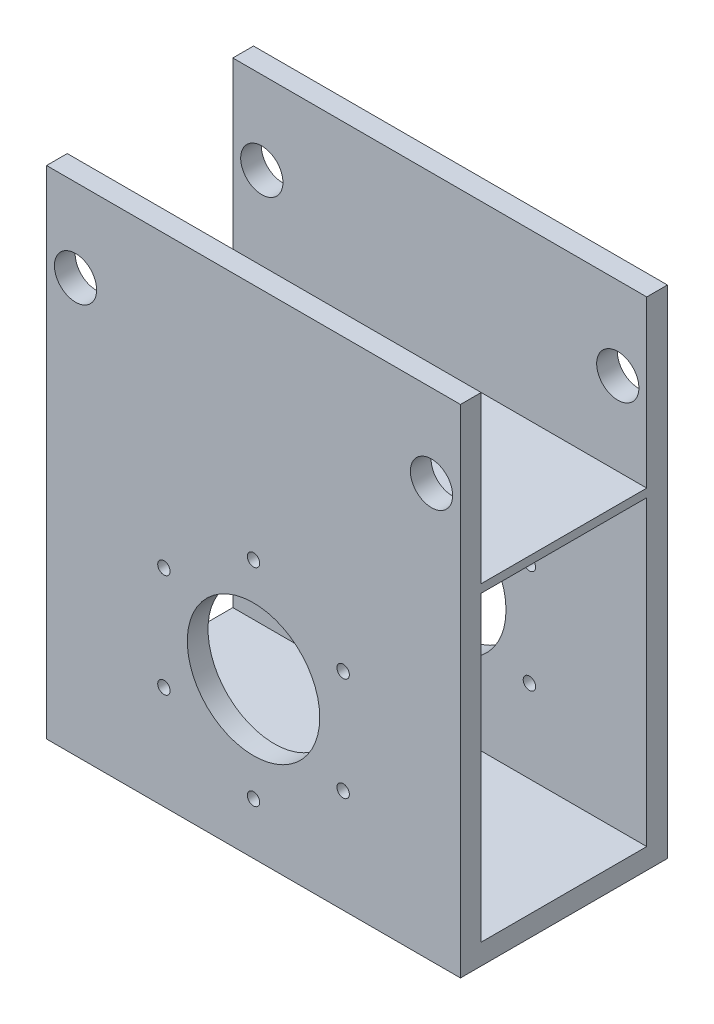
SolidWorks part; units mm, degrees
ref_plane "Front Plane" through (0, 0, 0) normal (0, 0, 1) x (1, 0, 0)
ref_plane "Top Plane" through (0, 0, 0) normal (0, 1, 0) x (1, 0, 0)
ref_plane "Right Plane" through (0, 0, 0) normal (1, 0, 0) x (0, 0, -1)
sketch "Sketch1" plane through (0, 0, 0) normal (0, 0, 1) x (1, 0, 0)
  line L1 (-50, 60) -> (50, 60)
  line L2 (-50, 60) -> (-50, -60)
  line L3 (-50, -60) -> (50, -60)
  line L4 (50, 60) -> (50, -60)
  line L5 (-50, 60) -> (50, -60) construction
  line L6 (-50, -60) -> (50, 60) construction
  point P0 (0, 0)
  dimension "D1" = 100
  dimension "D2" = 120
extrude "Boss-Extrude1" add sketch "Sketch1" along normal blind 5
sketch "Sketch2" plane through (0, 0, 5) normal (0, 0, 1) x (1, 0, 0)
  line L0 (-50, 60) -> (-50, -60) construction
  line L1 (-50, 20) -> (50, 20)
  line L2 (-50, 20) -> (-50, 18)
  line L3 (-50, 18) -> (50, 18)
  line L4 (50, 20) -> (50, 18)
  line L5 (50, -60) -> (50, 60) construction
  line L6 (50, 60) -> (-50, 60) construction
  dimension "D1" = 2
  dimension "D2" = 40
extrude "Boss-Extrude2" add sketch "Sketch2" along normal blind 45
sketch "Sketch3" plane through (0, 20, 0) normal (0, 1, 0) x (1, 0, 0)
  line L0 (50, -50) -> (50, -5) construction
  line L1 (-50, -50) -> (50, -50)
  line L2 (-50, -50) -> (-50, -45)
  line L3 (-50, -45) -> (50, -45)
  line L4 (50, -50) -> (50, -45)
  dimension "D1" = 5
extrude "Boss-Extrude3" add sketch "Sketch3" along normal blind 40 and the other way blind 60
sketch "Sketch6" plane through (0, -40, 0) normal (0, -1, 0) x (1, 0, 0)
  line L1 (-50, 45) -> (50, 45)
  line L2 (-50, 45) -> (-50, 50)
  line L3 (-50, 50) -> (50, 50)
  line L4 (50, 45) -> (50, 50)
  line L5 (-50, 0) -> (50, 0)
  line L6 (-50, 0) -> (-50, 5)
  line L7 (-50, 5) -> (50, 5)
  line L8 (50, 0) -> (50, 5)
extrude "Boss-Extrude4" add sketch "Sketch6" along normal blind 15
sketch "Sketch7" plane through (0, 0, 5) normal (0, 0, 1) x (1, 0, 0)
  line L6 (50, -60) -> (50, 18) construction
  line L7 (-50, -60) -> (50, -60)
  line L8 (-50, -60) -> (-50, -55)
  line L9 (-50, -55) -> (50, -55)
  line L10 (50, -60) -> (50, -55)
  dimension "D1" = 5
extrude "Boss-Extrude5" add sketch "Sketch7" along normal blind 45
sketch "Sketch8" plane through (0, 0, 50) normal (0, 0, 1) x (1, 0, 0)
  line L0 (-50, 15) -> (50, 15) construction
  line L1 (-50, 60) -> (-50, -60) construction
  line L2 (50, -60) -> (50, 60) construction
  line L3 (-50, -60) -> (50, -60) construction
  circle A1 centre (0, -22.5) radius 16
  circle A2 centre (0, -22.5) radius 25 construction
  circle A3 centre (0, 2.5) radius 1.5
  circle A4 centre (21.6506, -10) radius 1.5
  circle A5 centre (21.6506, -35) radius 1.5
  circle A6 centre (0, -47.5) radius 1.5
  circle A7 centre (-21.6506, -35) radius 1.5
  circle A8 centre (-21.6506, -10) radius 1.5
  point P26 (0, -22.5)
  dimension "D1" = 32
  dimension "D4" = 50
  dimension "D2" = 37.5
  dimension "D3" = 75
extrude "Cut-Extrude1" cut sketch "Sketch8" against normal through all
sketch "Sketch9" plane through (0, 0, 50) normal (0, 0, 1) x (1, 0, 0)
  line L0 (0, 60) -> (0, -60) construction
  line L1 (-50, 60) -> (50, 60) construction
  line L2 (-50, -60) -> (50, -60) construction
sketch "Sketch10" plane through (0, 0, 50) normal (0, 0, 1) x (1, 0, 0)
  line L1 (-50, 60) -> (50, 60) construction
  line L3 (0, 60) -> (0, -60) construction
  circle A0 centre (-43, 40) radius 5.1
  circle A1 centre (43, 40) radius 5.1
  dimension "D1" = 10.2
  dimension "D2" = 10.2
  dimension "D3" = 86
  dimension "D4" = 43
  dimension "D5" = 20
  dimension "D6" = 20
extrude "Cut-Extrude2" cut sketch "Sketch10" against normal through all
